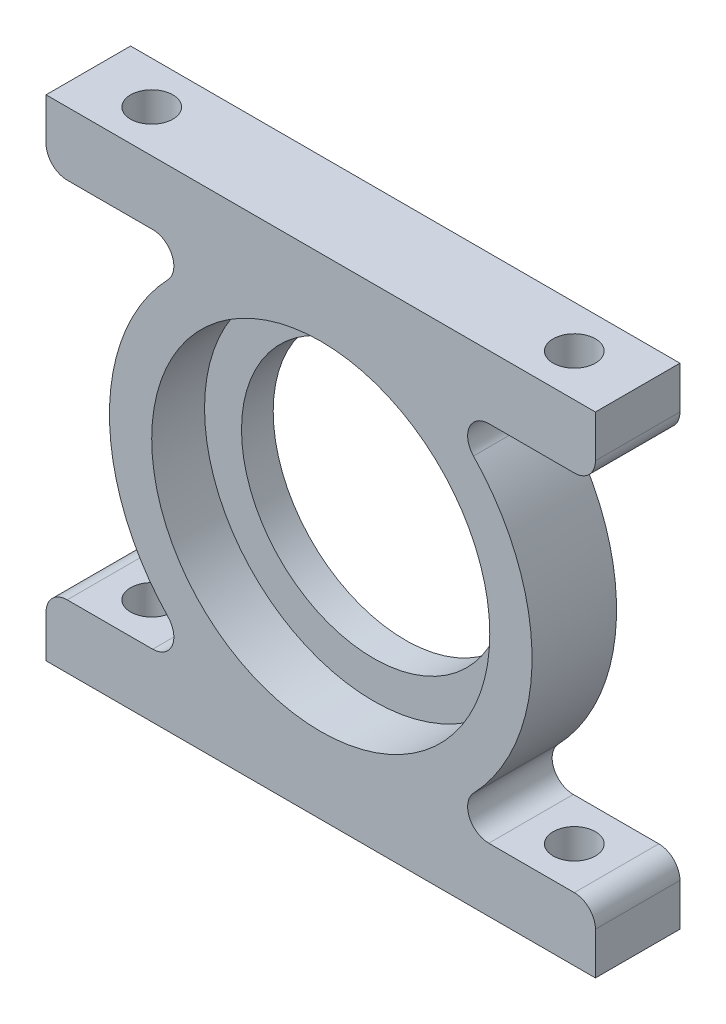
SolidWorks part; units mm, degrees
material "6061 合金"
ref_plane "前视基准面" through (0, 0, 0) normal (0, 0, 1) x (1, 0, 0)
ref_plane "上视基准面" through (0, 0, 0) normal (0, 1, 0) x (1, 0, 0)
ref_plane "右视基准面" through (0, 0, 0) normal (1, 0, 0) x (0, 0, -1)
sketch "草图1" plane through (0, 0, 0) normal (0, 0, 1) x (1, 0, 0)
  line L0 (-26, 23.2) -> (26, 23.2)
  line L1 (0, 0) -> (0, 32.4264) construction
  line L2 (-26, 23.2) -> (-26, 17.2)
  line L3 (-26, 17.2) -> (-10.2059, 17.2)
  line L4 (26, 23.2) -> (26, 17.2)
  line L5 (26, 17.2) -> (10.2059, 17.2)
  line L6 (0, 0) -> (-40.7009, 0) construction
  line L7 (26, -17.2) -> (10.2059, -17.2)
  line L8 (26, -23.2) -> (26, -17.2)
  line L9 (-26, -17.2) -> (-10.2059, -17.2)
  line L10 (-26, -23.2) -> (-26, -17.2)
  line L11 (-26, -23.2) -> (26, -23.2)
  circle A0 centre (0, 0) radius 16
  arc A1 (-10.2059, 17.2) -> (-10.2059, -17.2) centre (0, 0) ccw
  arc A2 (10.2059, -17.2) -> (10.2059, 17.2) centre (0, 0) ccw
  dimension "D1" = 32
  dimension "D3" = 40
  dimension "D2" = 23.2
  dimension "D4" = 6
  dimension "D5" = 26
  dimension "D6" = 6
  dimension "D7" = 26
extrude "凸台-拉伸1" add sketch "草图1" along normal blind 8
sketch "草图2" plane through (0, 23.2, 0) normal (0, 1, 0) x (1, 0, 0)
  line L0 (0, 0) -> (0, -8) construction
  line L1 (26, -8) -> (-26, -8) construction
  line L2 (-26, -4) -> (26, -4) construction
  line L3 (-26, -8) -> (-26, 0) construction
  line L4 (26, -8) -> (26, 0) construction
  circle A0 centre (-20, -4) radius 2
  circle A1 centre (20, -4) radius 2
  dimension "D1" = 4
  dimension "D2" = 20
extrude "切除-拉伸1" cut sketch "草图2" against normal blind 6
sketch "草图3" plane through (0, -23.2, 0) normal (0, -1, 0) x (1, 0, 0)
  circle A0 centre (20, 4) radius 2 construction
  circle A1 centre (-20, 4) radius 2 construction
  circle A2 centre (20, 4) radius 2
  circle A3 centre (-20, 4) radius 2
extrude "切除-拉伸2" cut sketch "草图3" against normal blind 6
fillet "圆角1" radius 2 4 edges at (-10.2059, -17.2, 4) (10.2059, -17.2, 4) (10.2059, 17.2, 4) (-10.2059, 17.2, 4)
fillet "圆角2" radius 2 4 edges at (-26, -17.2, 4) (26, -17.2, 4) (26, 17.2, 4) (-26, 17.2, 4)
sketch "草图4" plane through (0, 0, 0) normal (0, 0, -1) x (-1, 0, 0)
  circle A0 centre (0, 0) radius 16
  circle A1 centre (0, 0) radius 12.5
  dimension "D1" = 32
  dimension "D2" = 25
extrude "凸台-拉伸2" add sketch "草图4" against normal blind 3
